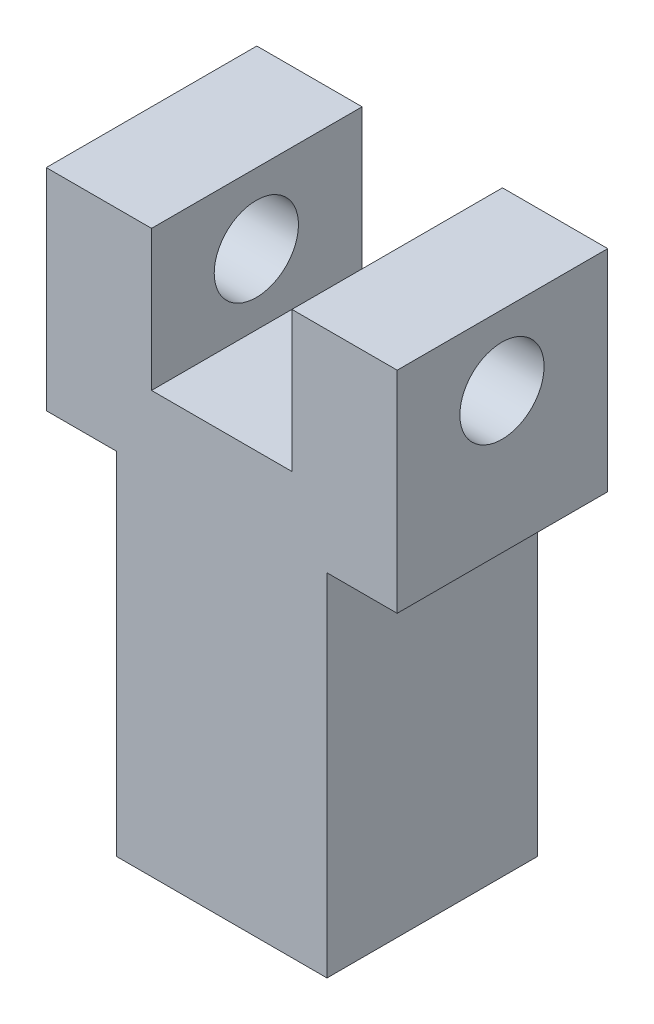
SolidWorks part; units mm, degrees
ref_plane "Front Plane" through (0, 0, 0) normal (0, 0, 1) x (1, 0, 0)
ref_plane "Top Plane" through (0, 0, 0) normal (0, 1, 0) x (1, 0, 0)
ref_plane "Right Plane" through (0, 0, 0) normal (1, 0, 0) x (0, 0, -1)
sketch "Sketch1" plane through (0, 0, 0) normal (0, 0, 1) x (1, 0, 0)
  line L0 (3.6876, 3.9348) -> (3.6876, -6.0652)
  line L1 (-13.8124, 3.9348) -> (-6.3124, 3.9348)
  line L2 (-13.8124, 3.9348) -> (-13.8124, -11.0652)
  line L3 (-13.8124, -11.0652) -> (11.1876, -11.0652)
  line L4 (11.1876, 3.9348) -> (11.1876, -11.0652)
  line L5 (3.6876, -6.0652) -> (-6.3124, -6.0652)
  line L6 (-6.3124, -6.0652) -> (-6.3124, 3.9348)
  line L7 (3.6876, 3.9348) -> (11.1876, 3.9348)
  dimension "D1" = 25
  dimension "D2" = 15
  dimension "D3" = 10
  dimension "D4" = 10
  dimension "D5" = 7.5
extrude "Boss-Extrude1" add sketch "Sketch1" along normal blind 15
sketch "Sketch2" plane through (11.1876, 0, 0) normal (1, 0, 0) x (0, 0, -1)
  line L0 (-15, 3.9348) -> (0, 3.9348) construction
  circle A0 centre (-7.5349, -1.0652) radius 3
  dimension "D1" = 6
  dimension "D2" = 5
extrude "Cut-Extrude1" cut sketch "Sketch2" against normal blind 35
sketch "Sketch3" plane through (0, -11.0652, 0) normal (0, -1, 0) x (1, 0, 0)
  line L0 (-13.8124, 0) -> (11.1876, 0) construction
  line L1 (-8.8124, 15) -> (6.1876, 15)
  line L2 (-8.8124, 15) -> (-8.8124, 0)
  line L3 (-8.8124, 0) -> (6.1876, 0)
  line L4 (6.1876, 15) -> (6.1876, 0)
  line L6 (-13.8124, 15) -> (-13.8124, 0) construction
  line L7 (3.6876, 9.9156) -> (-6.3124, 9.9156)
  line L12 (3.6876, 9.9156) -> (3.6876, 4.9156)
  line L13 (3.6876, 4.9156) -> (-6.3124, 4.9156)
  line L14 (-6.3124, 9.9156) -> (-6.3124, 4.9156)
  dimension "D1" = 15
  dimension "D2" = 15
  dimension "D3" = 5
  dimension "D4" = 10
  dimension "D5" = 5
  dimension "D6" = 2.5
extrude "Boss-Extrude2" add sketch "Sketch3" along normal blind 25
sketch "Sketch5" plane through (-8.8124, 0, 0) normal (-1, 0, 0) x (0, 0, 1)
  line L0 (15, -36.0652) -> (0, -36.0652) construction
  line L3 (0, -36.0652) -> (0, -11.0652) construction
  circle A0 centre (7.5, -23.5652) radius 3
  point P6 (0, -23.6462)
  point P7 (0, -23.2342)
  dimension "D1" = 6
  dimension "D2" = 12.5
  dimension "D3" = 7.5
extrude "Cut-Extrude3" cut sketch "Sketch5" against normal blind 7
